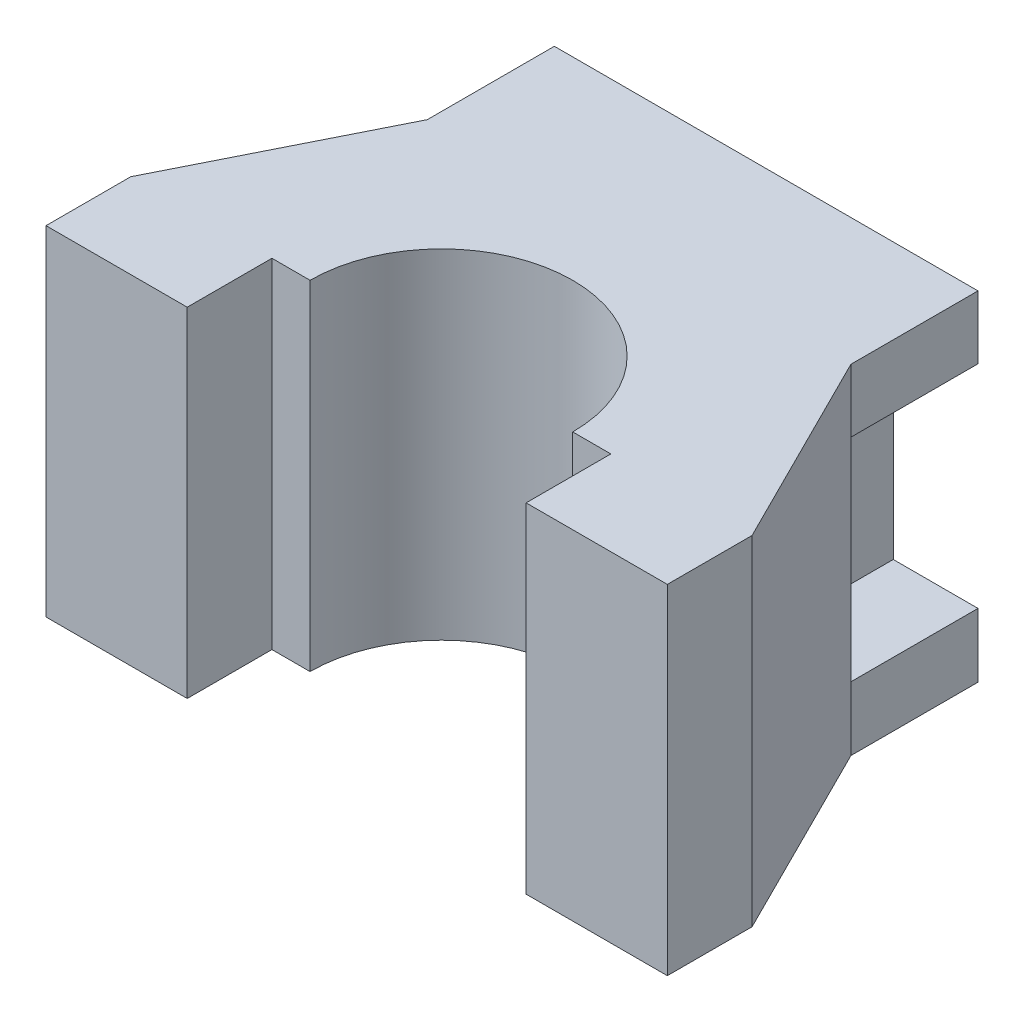
SolidWorks part; units mm, degrees
ref_plane "Front Plane" through (0, 0, 0) normal (0, 0, 1) x (1, 0, 0)
ref_plane "Top Plane" through (0, 0, 0) normal (0, 1, 0) x (1, 0, 0)
ref_plane "Right Plane" through (0, 0, 0) normal (1, 0, 0) x (0, 0, -1)
sketch "Sketch1" plane through (0, 0, 0) normal (0, 1, 0) x (1, 0, 0)
  line L0 (0, -55) -> (0, 55) construction
  line L1 (-44, 0) -> (-24, 0)
  line L2 (-44, 0) -> (-44, 12)
  line L4 (-24, 0) -> (-24, 12)
  line L5 (24, 0) -> (24, 12)
  line L6 (44, 0) -> (44, 12)
  line L7 (44, 0) -> (24, 0)
  line L8 (-24, 12) -> (-18.6018, 12)
  line L9 (24, 12) -> (18.6018, 12)
  line L10 (-44, 12) -> (-30, 40)
  line L11 (-30, 40) -> (-30, 58)
  line L12 (-30, 58) -> (30, 58)
  line L13 (30, 58) -> (30, 40)
  line L14 (30, 40) -> (44, 12)
  arc A1 (18.6018, 12) -> (-18.6018, 12) centre (0, 12) ccw
  point P13 (0, 58)
  point P18 (0, 30.6018)
  dimension "D3" = 60
  dimension "D1" = 48
  dimension "D2" = 88
  dimension "D4" = 58
  dimension "D5" = 18
  dimension "D6" = 18
  dimension "D7" = 12
  dimension "D8" = 12
extrude "Boss-Extrude1" add sketch "Sketch1" against normal blind 48
sketch "Sketch2" plane through (0, 0, -58) normal (0, 0, -1) x (-1, 0, 0)
  line L6 (-30, -48) -> (-30, 0) construction
  line L7 (-30, -38.9456) -> (-18, -38.9456)
  line L9 (-30, -8.9456) -> (-18, -8.9456)
  line L10 (-18, -38.9456) -> (-18, -8.9456)
  line L13 (-30, -8.9456) -> (-30, -38.9456)
  point P0 (-30, -24)
  dimension "D1" = 30
  dimension "D2" = 12
extrude "Cut-Extrude1" cut sketch "Sketch2" against normal blind 18
mirror "Mirror1" about plane through (0, 0, 0) normal (1, 0, 0) of "Cut-Extrude1"
